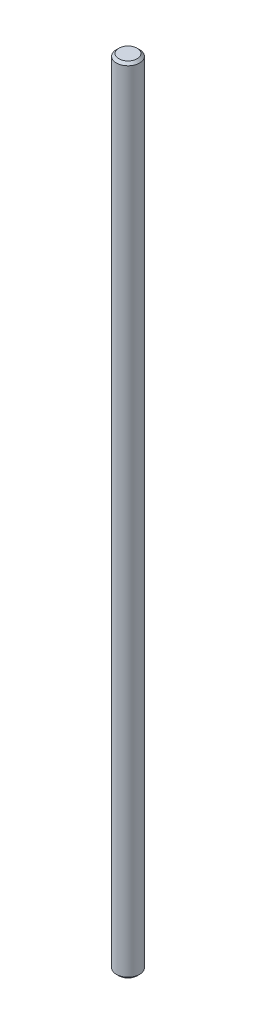
SolidWorks part; units mm, degrees
ref_plane "Front Plane" through (0, 0, 0) normal (0, 0, 1) x (1, 0, 0)
ref_plane "Top Plane" through (0, 0, 0) normal (0, 1, 0) x (1, 0, 0)
ref_plane "Right Plane" through (0, 0, 0) normal (1, 0, 0) x (0, 0, -1)
sketch "m4 diameter sketch" plane through (0, 0, 0) normal (0, 1, 0) x (1, 0, 0)
  circle A0 centre (0, 0) radius 1.9
  dimension "D1" = 3.8
extrude "Boss-Extrude1" add sketch "m4 diameter sketch" along normal blind 130
chamfer "Chamfer1" distance 0.4 angle 45 2 edges at (0, 0, 1.9) (0, 130, 1.9)
